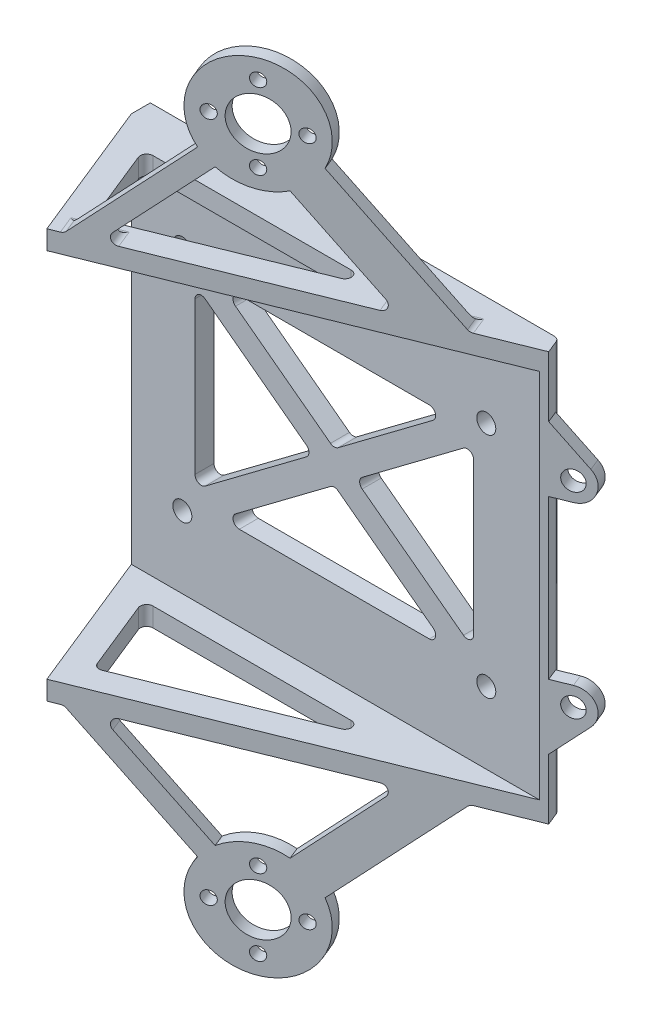
SolidWorks part; units mm, degrees
ref_plane "前视基准面" through (0, 0, 0) normal (0, 0, 1) x (1, 0, 0)
ref_plane "上视基准面" through (0, 0, 0) normal (0, 1, 0) x (1, 0, 0)
ref_plane "右视基准面" through (0, 0, 0) normal (1, 0, 0) x (0, 0, -1)
sketch "草图2" plane through (0, 0, 0) normal (0, 0, 1) x (1, 0, 0)
  line L5 (32.393, -32.3198) -> (-32.0526, -32.3198)
  line L6 (32.393, -32.3198) -> (32.393, 32.283)
  line L7 (32.393, 32.283) -> (-32.0526, 32.283)
  line L8 (-32.0526, -32.3198) -> (-32.0526, 32.283)
sketch "草图3" plane through (0, 0, 0) normal (0, 0, 1) x (1, 0, 0)
  circle A0 centre (24, -18) radius 1.5
  circle A1 centre (-24, -18) radius 1.5
  circle A2 centre (-24, 18) radius 1.5
  circle A3 centre (24, 18) radius 1.5
  dimension "D1" = 3
  dimension "D2" = 3
  dimension "D3" = 3
  dimension "D4" = 3
extrude "凸台-拉伸2" add sketch "草图2" along normal blind 3
extrude "切除-拉伸1" cut sketch "草图3" along normal blind 4
sketch "草图9" plane through (0, 32.283, 0) normal (0, 1, 0) x (1, 0, 0)
  line L1 (-32.0526, -3) -> (32.393, -3)
  line L5 (-32.0526, -3) -> (-23.0089, -25.3838)
  line L6 (-23.0089, -25.3838) -> (32.393, -3)
  line L7 (-20.7986, -20.1767) -> (11.8148, -7)
  line L8 (-26.1223, -7) -> (11.8148, -7)
  line L9 (-26.1223, -7) -> (-20.7986, -20.1767)
  dimension "D1" = 22
  dimension "D2" = 4
extrude "凸台-拉伸3" add sketch "草图9" against normal blind 3
sketch "草图10" plane through (0, -32.3198, 0) normal (0, -1, 0) x (1, 0, 0)
  line L0 (-23.0089, 25.3838) -> (-32.0526, 3)
  line L1 (-32.0526, 3) -> (32.393, 3)
  line L2 (32.393, 3) -> (-23.0089, 25.3838)
  line L4 (25.5, 3) -> (22.5, 3) construction
  line L5 (-23.0089, 25.3838) -> (32.393, 3) construction
  line L6 (11.8148, 7) -> (-20.7986, 20.1767)
  line L7 (-20.7986, 20.1767) -> (-26.1223, 7)
  line L8 (-26.1223, 7) -> (11.8148, 7)
  line L10 (-32.0526, 0) -> (32.393, 0) construction
  point P3 (0, 0)
  point P6 (0, 0)
  point P7 (0, 0)
  point P8 (0, 0)
  point P9 (0, 0)
  point P14 (0, 0)
  point P15 (0, 0)
  point P17 (0, 0)
  point P18 (0, 0)
  dimension "D1" = 4
extrude "凸台-拉伸4" add sketch "草图10" against normal blind 3
sketch "草图13" plane through (0, 32.283, 0) normal (0, 1, 0) x (1, 0, 0)
  line L0 (32.393, -3) -> (33.435, -2.579)
  line L1 (33.435, -2.579) -> (32.393, 0)
  line L2 (-23.0089, -25.3838) -> (32.393, -3) construction
  line L3 (32.393, -3) -> (32.393, 0)
  dimension "D1" = 2.7816
extrude "凸台-拉伸6" add sketch "草图13" against normal up to surface (64.6028 mm away) contours L3 L1 L0 up to face at (-4.4656, -32.3198, 6.2768)
sketch "草图11" plane through (5.5877, 0, 13.8301) normal (0.3746, 0, 0.9272) x (0.9272, 0, -0.3746)
  line L0 (-5.2157, 59.7316) -> (-5.2157, 47.7316) construction
  line L1 (0.7843, 53.7316) -> (-11.2157, 53.7316) construction
  line L2 (-5.2157, -47.7684) -> (-5.2157, -59.7684) construction
  line L3 (0.7843, -53.7684) -> (-11.2157, -53.7684) construction
  line L4 (-30.8425, -0.0184) -> (30.0343, -0.0184) construction
  line L7 (-0.966, 29.283) -> (-0.966, -29.3198) construction
  line L8 (28.9105, 29.283) -> (-30.8425, 29.283) construction
  line L9 (28.9105, -29.3198) -> (-30.8425, -29.3198) construction
  line L10 (33.0343, 15.4816) -> (33.0343, -15.5184) construction
  line L11 (-5.2157, 53.7316) -> (-5.2157, -53.7684) construction
  line L12 (-5.2157, 53.7316) -> (33.0343, 15.4816) construction
  line L13 (33.0343, -15.5184) -> (-5.2157, -53.7684) construction
  line L14 (0.7843, 53.7316) -> (-5.2157, 47.7316) construction
  line L15 (-11.2157, 53.7316) -> (-5.2157, 47.7316) construction
  line L16 (-11.2157, -53.7684) -> (-5.2157, -47.7684) construction
  line L17 (-5.2157, -53.7684) -> (-58.9657, -0.0184) construction
  line L18 (-58.9657, -0.0184) -> (-5.2157, 53.7316) construction
  line L19 (-12.5513, 48.5173) -> (-28.7856, 32.283)
  line L20 (2.9056, -49.8897) -> (35.1556, -17.6397)
  line L21 (-1.337, -45.6471) -> (30.913, -13.3971)
  line L22 (35.1556, 17.6029) -> (2.9056, 49.8529)
  line L23 (30.913, 13.3603) -> (-1.337, 45.6103)
  line L24 (-24.543, 32.283) -> (-10.43, 46.396)
  line L25 (-24.543, -32.3198) -> (-10.43, -46.4328)
  line L26 (-28.7856, -32.3198) -> (-12.5513, -48.5541)
  line L27 (30.0343, -32.3198) -> (-30.8425, -32.3198) construction
  line L28 (-30.8425, 32.283) -> (30.0343, 32.283) construction
  line L29 (-28.7856, -32.3198) -> (-24.543, -32.3198)
  line L30 (-24.543, 32.283) -> (-28.7856, 32.283)
  line L31 (14.9902, -29.3198) -> (23.4755, -29.3198)
  line L32 (20.4755, -32.3198) -> (11.9902, -32.3198)
  line L33 (23.4755, 29.283) -> (14.9902, 29.283)
  line L34 (20.4755, 32.283) -> (11.9902, 32.283)
  line L35 (30.0343, -32.3198) -> (30.0343, 32.283) construction
  line L36 (-30.8425, 29.283) -> (-30.8425, -29.3198) construction
  line L37 (-30.8425, -29.3198) -> (28.9105, -29.3198) construction
  line L38 (33.0343, 12.4816) -> (30.0343, 12.4816)
  line L39 (33.0343, -12.5184) -> (30.0343, -12.5184)
  circle A0 centre (-5.2157, 53.7316) radius 6 construction
  circle A1 centre (-11.2157, 53.7316) radius 1.05
  circle A2 centre (-5.2157, 53.7316) radius 4
  circle A3 centre (-5.2157, 59.7316) radius 1.05
  circle A4 centre (0.7843, 53.7316) radius 1.05
  circle A5 centre (-5.2157, 47.7316) radius 1.05
  circle A6 centre (-5.2157, 53.7316) radius 9
  circle A7 centre (-5.2157, -53.7684) radius 6 construction
  circle A8 centre (-11.2157, -53.7684) radius 1.05
  circle A9 centre (-5.2157, -53.7684) radius 4
  circle A10 centre (-5.2157, -47.7684) radius 1.05
  circle A11 centre (0.7843, -53.7684) radius 1.05
  circle A12 centre (-5.2157, -59.7684) radius 1.05
  circle A13 centre (-5.2157, -53.7684) radius 9
  circle A14 centre (33.0343, 15.4816) radius 1.55
  circle A15 centre (33.0343, -15.5184) radius 1.55
  circle A16 centre (33.0343, 15.4816) radius 3
  circle A17 centre (33.0343, -15.5184) radius 3
  point P41 (-0.4041, -0.0184)
  point P52 (33.0343, -0.0184)
  point P53 (-5.2157, -0.0184)
  line M14 (30.0343, 32.283) -> (-30.8425, 32.283)
  line M82 (-30.8425, -32.3198) -> (30.0343, -32.3198)
  line M83 (30.0343, -32.3198) -> (30.0343, 32.283)
  dimension "D1" = 2.1
  dimension "D2" = 2.1
  dimension "D3" = 2.1
  dimension "D4" = 2.1
  dimension "D5" = 18
  dimension "D6" = 12
  dimension "D7" = 8
  dimension "D8" = 2.1
  dimension "D9" = 2.1
  dimension "D10" = 2.1
  dimension "D11" = 2.1
  dimension "D12" = 18
  dimension "D13" = 12
  dimension "D14" = 8
  dimension "D15" = 3.1
  dimension "D16" = 3.1
  dimension "D21" = 6
  dimension "D22" = 6
  dimension "D17" = 31
  dimension "D18" = 107.5
  dimension "D19" = 38.25
  dimension "D20" = 135
  dimension "D24" = 6
  dimension "D25" = 6
  dimension "D26" = 1.5
  dimension "D27" = 1.5
  dimension "D28" = 1.5
  dimension "D29" = 1.5
extrude "凸台-拉伸7" add sketch "草图11" against normal blind 2 contours A16 L23 L38 M83 | A16 A14 | A16 L23 M83 | A16 L22 M83 | A17 A15 | A17 L21 M83 | A17 L39 L21 M83 | A17 L20 M83 | A13 L20 L21 M82 | A13 A8 A9 A10 A11 A12 | A13 L25 L26 M82 | A6 L23 L22 M14 | A6 L19 L24 M14 | A6 A1 A2 A3 A4 A5
fillet "圆角1" radius 1 1 edges at (32.393, -0.0184, 0)
fillet "圆角2" radius 1 12 edges at (-17.5428, 32.283, 22.0968) (-21.4765, 32.283, 23.6862) (-19.8842, 32.283, 21.9643) (16.3303, 32.283, 8.4112) (24.1977, 32.283, 5.2326) (19.8894, 32.283, 5.8947) (-17.5428, -32.3198, 22.0968) (16.3303, -32.3198, 8.4112) (-21.4765, -32.3198, 23.6862) (-19.8842, -32.3198, 21.9643) (19.8894, -32.3198, 5.8947) (24.1977, -32.3198, 5.2326)
fillet "圆角3" radius 1 6 edges at (-26.1223, -30.8198, 7) (-20.7986, -30.8198, 20.1767) (-26.1223, 30.783, 7) (-20.7986, 30.783, 20.1767) (11.8148, 30.783, 7) (11.8148, -30.8198, 7)
sketch "草图15" plane through (0, 0, 3) normal (0, 0, 1) x (1, 0, 0)
  line L0 (-24, 18) -> (-24, -18) construction
  line L1 (24, 18) -> (24, -18) construction
  line L2 (24, -18) -> (-24, -18) construction
  line L3 (-24, 18) -> (24, 18) construction
  line L4 (24, 18) -> (-24, -18) construction
  line L5 (-24, 18) -> (24, -18) construction
  line L6 (-18, 16) -> (18, 16)
  line L7 (18, 16) -> (0, 2.5)
  line L8 (0, 2.5) -> (-18, 16)
  line L9 (-22, 14) -> (-3.3333, 0)
  line L10 (-3.3333, 0) -> (-22, -14)
  line L11 (-22, -14) -> (-22, 14)
  line L12 (-18, -16) -> (18, -16)
  line L13 (18, -16) -> (0, -2.5)
  line L14 (0, -2.5) -> (-18, -16)
  line L16 (22, 14) -> (3.3333, 0)
  line L17 (3.3333, 0) -> (22, -14)
  line L18 (22, -14) -> (22, 14)
  dimension "D1" = 2
  dimension "D2" = 2
  dimension "D3" = 2
  dimension "D4" = 2
  dimension "D5" = 2
  dimension "D6" = 2
  dimension "D7" = 2
  dimension "D8" = 2
  dimension "D9" = 2
  dimension "D10" = 2
extrude "切除-拉伸3" cut sketch "草图15" against normal through all
fillet "圆角5" radius 1 12 edges at (-18, -16, 1.5) (18, -16, 1.5) (22, -14, 1.5) (22, 14, 1.5) (-3.3333, 0, 1.5) (-22, -14, 1.5) (0, 2.5, 1.5) (3.3333, 0, 1.5) (-18, 16, 1.5) (0, -2.5, 1.5) (-22, 14, 1.5) (18, 16, 1.5)
